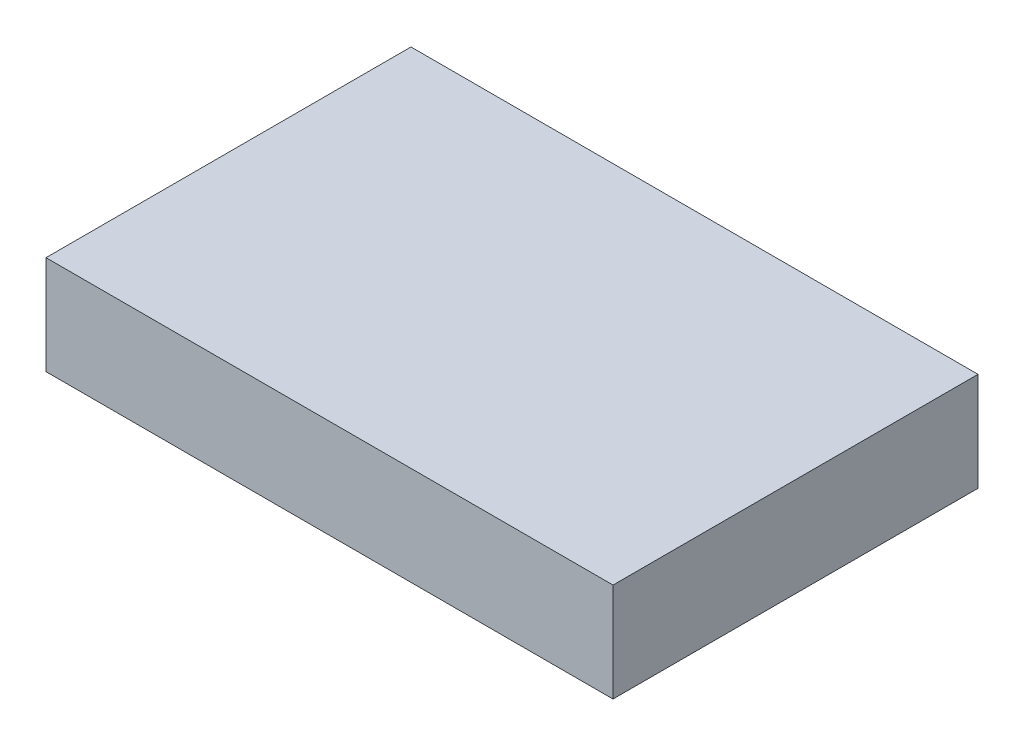
SolidWorks part; units mm, degrees
ref_plane "Спереди" through (0, 0, 0) normal (0, 0, 1) x (1, 0, 0)
ref_plane "Сверху" through (0, 0, 0) normal (0, 1, 0) x (1, 0, 0)
ref_plane "Справа" through (0, 0, 0) normal (1, 0, 0) x (0, 0, -1)
other "Configuration Table"
sketch "Эскиз1" plane through (0, 0, 0) normal (0, 1, 0) x (1, 0, 0)
  line L1 (43.5, -28) -> (-43.5, -28)
  line L2 (43.5, -28) -> (43.5, 28)
  line L3 (43.5, 28) -> (-43.5, 28)
  line L4 (-43.5, -28) -> (-43.5, 28)
  line L5 (43.5, -28) -> (-43.5, 28) construction
  line L6 (43.5, 28) -> (-43.5, -28) construction
  point P0 (0, 0)
extrude "Бобышка-Вытянуть1" add sketch "Эскиз1" along normal blind 15.15
sketch "Эскиз2" plane through (0, 0, 0) normal (0, -1, 0) x (1, 0, 0)
  circle A1 centre (40, 24.5) radius 1.3645
  circle A2 centre (40.0327, -18.4511) radius 1.5
  circle A3 centre (40, -24.5) radius 1.3645
  circle A4 centre (-18.0855, -24.5) radius 1.3645
  circle A5 centre (-17.737, 18.3009) radius 1.5
  circle A6 centre (-18.0855, 24.5) radius 1.3645
extrude "Вырез-Вытянуть1" cut sketch "Эскиз2" against normal blind 10
